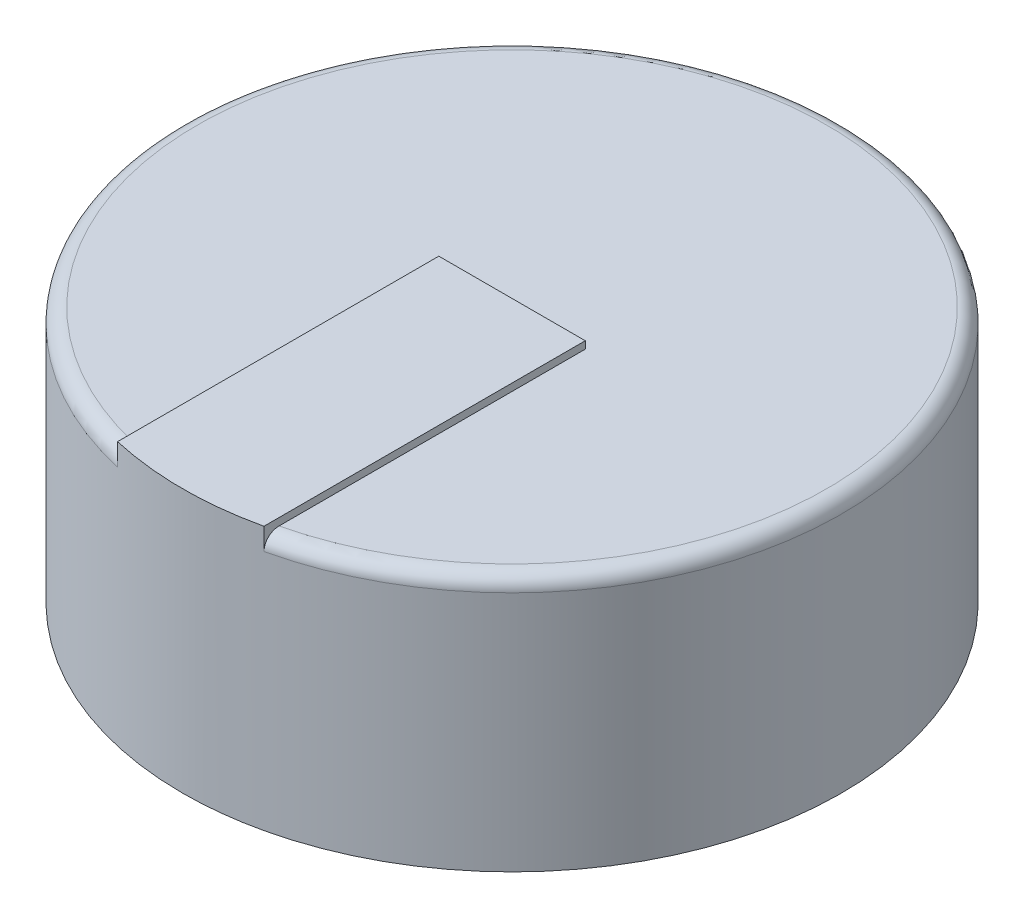
SolidWorks part; units mm, degrees
ref_plane "Front Plane" through (0, 0, 0) normal (0, 0, 1) x (1, 0, 0)
ref_plane "Top Plane" through (0, 0, 0) normal (0, 1, 0) x (1, 0, 0)
ref_plane "Right Plane" through (0, 0, 0) normal (1, 0, 0) x (0, 0, -1)
sketch "Sketch1" plane through (0, 0, 0) normal (0, 1, 0) x (1, 0, 0)
  circle A0 centre (0, 0) radius 5.715
  dimension "D1" = 11.43
extrude "Boss-Extrude1" add sketch "Sketch1" along normal blind 4.445
fillet "Fillet2" radius 0.254 1 edges at (0, 4.445, 5.715)
sketch "Sketch2" plane through (0, 0, 0) normal (0, -1, 0) x (1, 0, 0)
  line L0 (0, 5.715) -> (0, 0) construction
  line L1 (1.27, 5.715) -> (1.27, 0)
  line L2 (1.27, 0) -> (-1.27, 0)
  line L3 (-1.27, 0) -> (-1.27, 5.715)
  line L4 (-1.27, 5.715) -> (1.27, 5.715)
  circle A0 centre (0, 0) radius 5.715 construction
  dimension "D1" = 2.54
  dimension "D2" = 5.715
extrude "Cut-Extrude1" cut sketch "Sketch2" against normal through all
sketch "Sketch3" plane through (0, 0, 0) normal (0, -1, 0) x (1, 0, 0)
  line L0 (-1.27, 0) -> (-1.27, 5.5721)
  line L1 (-1.27, 0) -> (1.27, 0)
  line L2 (1.27, 0) -> (1.27, 5.5721)
  arc A0 (-1.27, 5.5721) -> (1.27, 5.5721) centre (0, 0) cw
  arc A1 (-1.27, 5.5721) -> (1.27, 5.5721) centre (0, 0) ccw construction
extrude "Boss-Extrude2" add sketch "Sketch3" against normal blind 4.572
